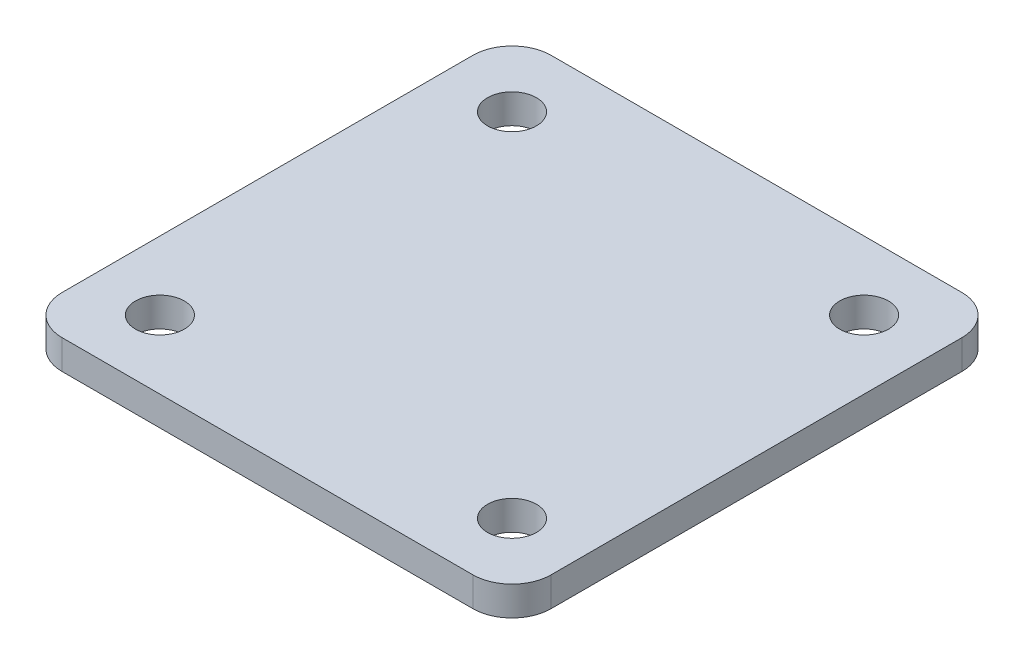
SolidWorks part; units mm, degrees
ref_plane "Front Plane" through (0, 0, 0) normal (0, 0, 1) x (1, 0, 0)
ref_plane "Top Plane" through (0, 0, 0) normal (0, 1, 0) x (1, 0, 0)
ref_plane "Right Plane" through (0, 0, 0) normal (1, 0, 0) x (0, 0, -1)
sketch "Sketch1" plane through (0, 0, 0) normal (0, 1, 0) x (1, 0, 0)
  line L1 (-25, 25) -> (25, 25)
  line L2 (-25, 25) -> (-25, -25)
  line L3 (-25, -25) -> (25, -25)
  line L4 (25, 25) -> (25, -25)
  line L5 (-25, 25) -> (25, -25) construction
  line L6 (-25, -25) -> (25, 25) construction
  point P0 (0, 0)
  dimension "D1" = 50
  dimension "D2" = 50
extrude "Boss-Extrude1" add sketch "Sketch1" along normal blind 3
fillet "Fillet1" radius 4 4 edges at (-25, 1.5, 25) (-25, 1.5, -25) (25, 1.5, -25) (25, 1.5, 25)
sketch "Sketch2" plane through (0, 3, 0) normal (0, 1, 0) x (1, 0, 0)
  circle A0 centre (-18, 18) radius 2.5
  circle A1 centre (18, 18) radius 2.5
  circle A2 centre (18, -18) radius 2.5
  circle A3 centre (-18, -18) radius 2.5
  point P8 (0, 0)
  point P10 (0, 0)
  point P11 (0, 0)
  point P12 (0, 0)
  point P13 (18, -18)
  dimension "D1" = 5
  dimension "D2" = 5
  dimension "D3" = 5
  dimension "D4" = 5
  dimension "D5" = 36
  dimension "D6" = 18
  dimension "D7" = 36
  dimension "D8" = 18
extrude "Cut-Extrude1" cut sketch "Sketch2" against normal blind 3
